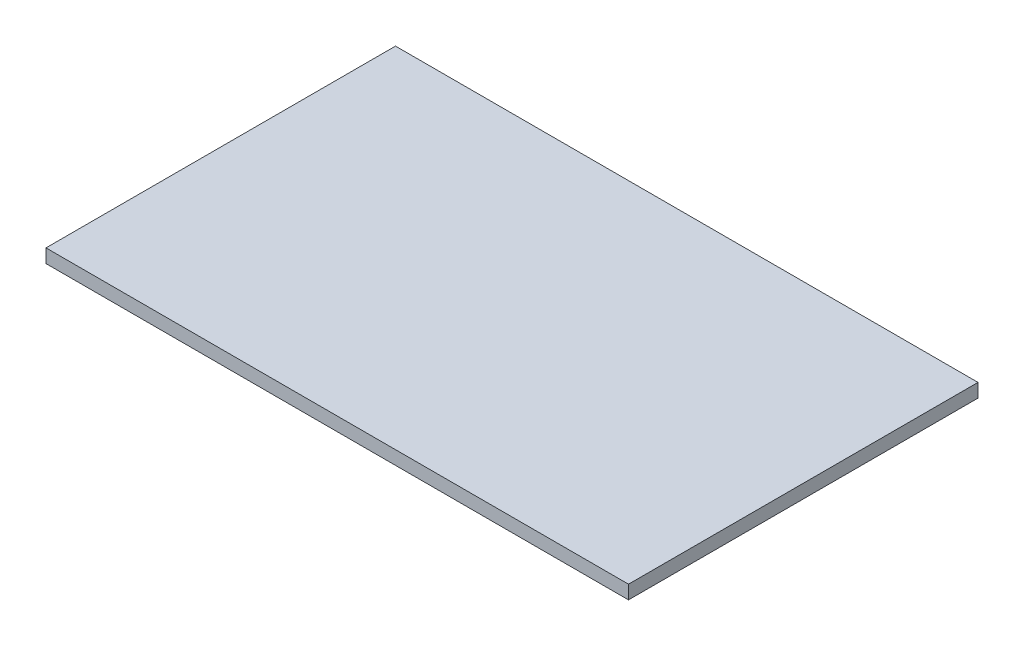
SolidWorks part; units mm, degrees
ref_plane "Front Plane" through (0, 0, 0) normal (0, 0, 1) x (1, 0, 0)
ref_plane "Top Plane" through (0, 0, 0) normal (0, 1, 0) x (1, 0, 0)
ref_plane "Right Plane" through (0, 0, 0) normal (1, 0, 0) x (0, 0, -1)
sketch "Sketch1" plane through (0, 0, 0) normal (0, 1, 0) x (1, 0, 0)
  line L1 (0, 0) -> (127, 0)
  line L2 (0, 0) -> (0, 76.2)
  line L3 (0, 76.2) -> (127, 76.2)
  line L4 (127, 0) -> (127, 76.2)
  dimension "D1" = 127
  dimension "D2" = 76.2
extrude "Boss-Extrude1" add sketch "Sketch1" along normal blind 2.9718
